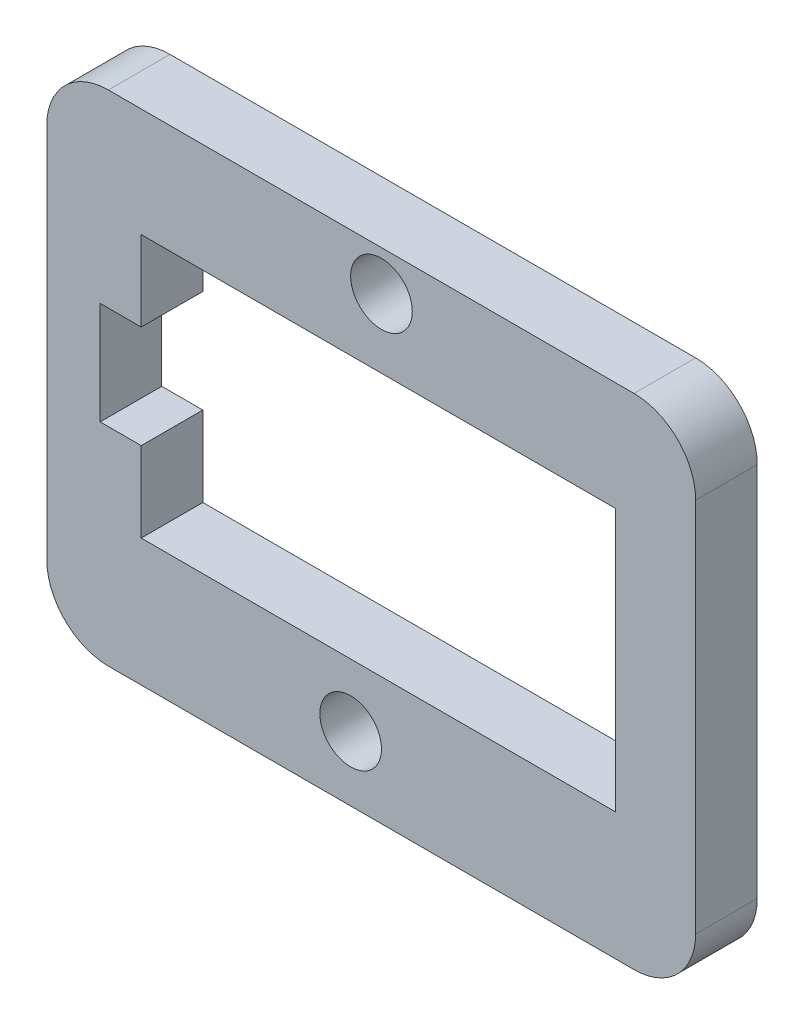
SolidWorks part; units mm, degrees
material "Balsa"
ref_plane "Front Plane" through (0, 0, 0) normal (0, 0, 1) x (1, 0, 0)
ref_plane "Top Plane" through (0, 0, 0) normal (0, 1, 0) x (1, 0, 0)
ref_plane "Right Plane" through (0, 0, 0) normal (1, 0, 0) x (0, 0, -1)
sketch "Sketch1" plane through (0, 0, 0) normal (0, 0, 1) x (1, 0, 0)
  line L12 (28.6, 0) -> (28.6, 18.3)
  line L13 (25.6, 21.3) -> (0, 21.3)
  line L14 (-3, 18.3) -> (-3, 0)
  line L15 (0, -3) -> (25.6, -3)
  line L20 (24.7, 3.2) -> (24.7, 16)
  line L21 (24.7, 16) -> (1.6, 16)
  line L22 (1.6, 16) -> (1.6, 12.1)
  line L23 (1.6, 12.1) -> (-0.4, 12.1)
  line L24 (-0.4, 12.1) -> (-0.4, 7.1)
  line L25 (-0.4, 7.1) -> (1.6, 7.1)
  line L26 (1.6, 7.1) -> (1.6, 3.2)
  line L27 (1.6, 3.2) -> (24.7, 3.2)
  circle A2 centre (11.8, 0.15) radius 1.5
  circle A3 centre (13.3, 19.35) radius 1.5
  arc A8 (25.6, -3) -> (28.6, 0) centre (25.6, 0) ccw
  arc A9 (28.6, 18.3) -> (25.6, 21.3) centre (25.6, 18.3) ccw
  arc A10 (0, 21.3) -> (-3, 18.3) centre (0, 18.3) ccw
  arc A11 (-3, 0) -> (0, -3) centre (0, 0) ccw
  dimension "D3" = 3
  dimension "D4" = 3
  dimension "D2" = 31.6
  dimension "D5" = 24.3
  dimension "D6" = 3.9
  dimension "D7" = 3.9
  dimension "D8" = 12.8
  dimension "D9" = 3.9
  dimension "D10" = 6.2
  dimension "D11" = 3.05
  dimension "D12" = 12.9
  dimension "D13" = 11.4
  dimension "D14" = 3.35
extrude "Boss-Extrude1" add sketch "Sketch1" along normal blind 3 contours L21 L22 L23 L24 L25 L26 L27 L20
